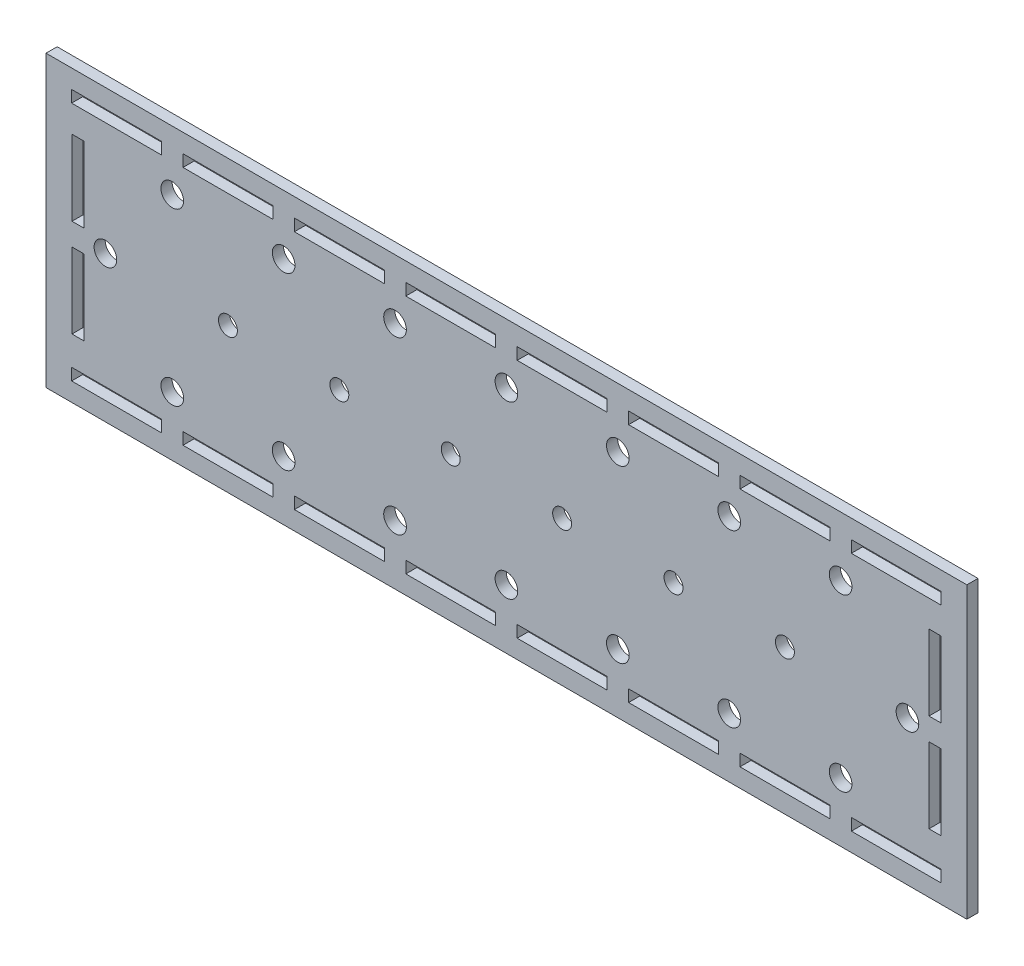
SolidWorks part; units mm, degrees
ref_plane "Front Plane" through (0, 0, 0) normal (0, 0, 1) x (1, 0, 0)
ref_plane "Top Plane" through (0, 0, 0) normal (0, 1, 0) x (1, 0, 0)
ref_plane "Right Plane" through (0, 0, 0) normal (1, 0, 0) x (0, 0, -1)
sketch "Sketch1" plane through (0, 0, 0) normal (0, 0, 1) x (-1, 0, 0)
  line L0 (-395.8872, 493) -> (-395.8872, 489.8)
  line L2 (-395.8872, 493) -> (-371.6872, 493)
  line L3 (-371.6872, 493) -> (-371.6872, 489.8)
  line L4 (-395.8872, 489.8) -> (-371.6872, 489.8)
  line L8 (-425.8872, 493) -> (-425.8872, 489.8)
  line L9 (-552.7872, 498) -> (-304.7872, 498)
  line L10 (-552.7872, 498) -> (-552.7872, 420)
  line L11 (-552.7872, 420) -> (-304.7872, 420)
  line L12 (-304.7872, 498) -> (-304.7872, 420)
  line L13 (-365.8872, 493) -> (-341.6872, 493)
  line L14 (-365.8872, 493) -> (-365.8872, 489.8)
  line L15 (-365.8872, 489.8) -> (-341.6872, 489.8)
  line L16 (-341.6872, 493) -> (-341.6872, 489.8)
  line L17 (-425.8872, 493) -> (-401.6872, 493)
  line L18 (-401.6872, 493) -> (-401.6872, 489.8)
  line L19 (-425.8872, 489.8) -> (-401.6872, 489.8)
  line L20 (-455.8872, 493) -> (-455.8872, 489.8)
  line L21 (-455.8872, 493) -> (-431.6872, 493)
  line L22 (-431.6872, 493) -> (-431.6872, 489.8)
  line L23 (-455.8872, 489.8) -> (-431.6872, 489.8)
  line L24 (-485.8872, 493) -> (-485.8872, 489.8)
  line L25 (-485.8872, 493) -> (-461.6872, 493)
  line L26 (-461.6872, 493) -> (-461.6872, 489.8)
  line L27 (-485.8872, 489.8) -> (-461.6872, 489.8)
  line L28 (-515.8872, 493) -> (-515.8872, 489.8)
  line L29 (-515.8872, 493) -> (-491.6872, 493)
  line L30 (-491.6872, 493) -> (-491.6872, 489.8)
  line L31 (-515.8872, 489.8) -> (-491.6872, 489.8)
  line L32 (-545.8872, 493) -> (-545.8872, 489.8)
  line L33 (-545.8872, 493) -> (-521.6872, 493)
  line L34 (-521.6872, 493) -> (-521.6872, 489.8)
  line L35 (-545.8872, 489.8) -> (-521.6872, 489.8)
  line L36 (-335.8872, 493) -> (-335.8872, 489.8)
  line L37 (-335.8872, 493) -> (-311.6872, 493)
  line L38 (-311.6872, 493) -> (-311.6872, 489.8)
  line L39 (-335.8872, 489.8) -> (-311.6872, 489.8)
  line L40 (-552.7872, 459) -> (-284.5954, 459) construction
  line L73 (-314.9872, 455.7) -> (-311.7872, 455.7)
  line L74 (-314.9872, 482) -> (-311.7872, 482)
  line L75 (-314.9872, 482) -> (-314.9872, 461.7)
  line L76 (-314.9872, 461.7) -> (-311.7872, 461.7)
  line L77 (-311.7872, 482) -> (-311.7872, 461.7)
  line L78 (-311.7872, 435.4) -> (-311.7872, 455.7)
  line L79 (-314.9872, 435.4) -> (-311.7872, 435.4)
  line L80 (-314.9872, 435.4) -> (-314.9872, 455.7)
  line L81 (-428.7872, 510.2561) -> (-428.7872, 380.3241) construction
  line L82 (-542.5872, 435.4) -> (-542.5872, 455.7)
  line L83 (-542.5872, 435.4) -> (-545.7872, 435.4)
  line L84 (-545.7872, 435.4) -> (-545.7872, 455.7)
  line L85 (-542.5872, 455.7) -> (-545.7872, 455.7)
  line L86 (-542.5872, 461.7) -> (-545.7872, 461.7)
  line L87 (-545.7872, 482) -> (-545.7872, 461.7)
  line L88 (-542.5872, 482) -> (-545.7872, 482)
  line L89 (-542.5872, 482) -> (-542.5872, 461.7)
  line L90 (-545.8872, 425) -> (-521.6872, 425)
  line L91 (-521.6872, 425) -> (-521.6872, 428.2)
  line L92 (-545.8872, 428.2) -> (-521.6872, 428.2)
  line L93 (-545.8872, 425) -> (-545.8872, 428.2)
  line L94 (-515.8872, 425) -> (-491.6872, 425)
  line L95 (-491.6872, 425) -> (-491.6872, 428.2)
  line L96 (-515.8872, 428.2) -> (-491.6872, 428.2)
  line L97 (-515.8872, 425) -> (-515.8872, 428.2)
  line L98 (-485.8872, 425) -> (-461.6872, 425)
  line L99 (-461.6872, 425) -> (-461.6872, 428.2)
  line L100 (-485.8872, 428.2) -> (-461.6872, 428.2)
  line L101 (-485.8872, 425) -> (-485.8872, 428.2)
  line L102 (-455.8872, 425) -> (-431.6872, 425)
  line L103 (-431.6872, 425) -> (-431.6872, 428.2)
  line L104 (-455.8872, 428.2) -> (-431.6872, 428.2)
  line L105 (-455.8872, 425) -> (-455.8872, 428.2)
  line L106 (-425.8872, 425) -> (-401.6872, 425)
  line L107 (-401.6872, 425) -> (-401.6872, 428.2)
  line L108 (-425.8872, 428.2) -> (-401.6872, 428.2)
  line L109 (-425.8872, 425) -> (-425.8872, 428.2)
  line L110 (-395.8872, 425) -> (-371.6872, 425)
  line L111 (-371.6872, 425) -> (-371.6872, 428.2)
  line L112 (-395.8872, 428.2) -> (-371.6872, 428.2)
  line L113 (-395.8872, 425) -> (-395.8872, 428.2)
  line L114 (-365.8872, 428.2) -> (-341.6872, 428.2)
  line L115 (-341.6872, 425) -> (-341.6872, 428.2)
  line L116 (-365.8872, 425) -> (-341.6872, 425)
  line L117 (-365.8872, 425) -> (-365.8872, 428.2)
  line L118 (-335.8872, 425) -> (-311.6872, 425)
  line L119 (-311.6872, 425) -> (-311.6872, 428.2)
  line L120 (-335.8872, 428.2) -> (-311.6872, 428.2)
  line L121 (-335.8872, 425) -> (-335.8872, 428.2)
  circle A16 centre (-338.7872, 436) radius 3.05
  circle A17 centre (-368.7872, 436) radius 3.05
  circle A18 centre (-428.7872, 436) radius 3.05
  circle A19 centre (-398.7872, 436) radius 3.05
  circle A20 centre (-488.7872, 436) radius 3.05
  circle A21 centre (-458.7872, 436) radius 3.05
  circle A22 centre (-458.7872, 482) radius 3.05
  circle A23 centre (-428.7872, 482) radius 3.05
  circle A24 centre (-398.7872, 482) radius 3.05
  circle A25 centre (-368.7872, 482) radius 3.05
  circle A26 centre (-338.7872, 482) radius 3.05
  circle A27 centre (-320.7872, 458.7) radius 3.05
  circle A28 centre (-488.7872, 482) radius 3.05
  circle A29 centre (-518.7872, 436) radius 3.05
  circle A30 centre (-536.7872, 459) radius 3.05
  circle A31 centre (-518.7872, 482) radius 3.05
  point P107 (-313.3872, 482)
  dimension "D4" = 16
  dimension "D11" = 3
  dimension "D1" = 16
  dimension "D2" = 16
  dimension "D3" = 7
  dimension "D5" = 2.9
  dimension "D6" = 2.9
  dimension "D7" = 5
  dimension "D8" = 3.2
  dimension "D14" = 3.2
  dimension "D9" = 7
  dimension "D10" = 2
extrude "Boss-Extrude2" add sketch "Sketch1" along normal blind 3
sketch "Sketch4" plane through (545.7872, 0, 0) normal (-1, 0, 0) x (0, 0, 1)
  line L0 (3, -427.6) -> (10, -427.6)
  line L3 (3, -427.6) -> (3, -435.4)
  line L4 (0, -435.4) -> (0, -455.7)
  line L5 (0, -455.7) -> (3, -455.7)
  line L6 (3, -455.7) -> (3, -435.4)
  line L7 (3, -435.4) -> (0, -435.4)
  line L8 (0, -435.4) -> (0, -455.7)
  line L9 (0, -455.7) -> (3, -455.7)
  line L11 (3, -435.4) -> (0, -435.4)
  line L12 (0, -461.7) -> (0, -482)
  line L13 (0, -482) -> (3, -482)
  line L14 (3, -482) -> (3, -461.7)
  line L15 (3, -461.7) -> (0, -461.7)
  line L17 (0, -482) -> (3, -482)
  line L19 (3, -461.7) -> (0, -461.7)
  line L20 (10, -427.6) -> (10, -489.8)
  line L22 (3, -455.7) -> (3, -461.7)
  line L23 (0, -461.7) -> (0, -482)
  line L24 (3, -482) -> (3, -489.8)
  line L25 (3, -489.8) -> (10, -489.8)
  dimension "D1" = 0
  dimension "D2" = 0
sketch "Sketch5" plane through (0, 0, 3) normal (0, 0, 1) x (1, 0, 0)
  line L0 (304.7872, -459) -> (559.3179, -459) construction
  line L1 (304.7872, -420) -> (304.7872, -498) construction
  line L2 (428.7872, -420) -> (428.7872, -508.4743) construction
  line L3 (552.7872, -420) -> (304.7872, -420) construction
  circle A2 centre (353.7872, -459) radius 2.55
  circle A4 centre (338.7872, -436) radius 3.05 construction
  circle A5 centre (383.7872, -459) radius 2.55
  circle A6 centre (413.7872, -459) radius 2.55
  circle A7 centre (443.7872, -459) radius 2.55
  circle A8 centre (473.7872, -459) radius 2.55
  circle A9 centre (503.7872, -459) radius 2.55
  dimension "D1" = 15
  dimension "D2" = 6
extrude "Cut-Extrude1" cut sketch "Sketch5" against normal blind 10
